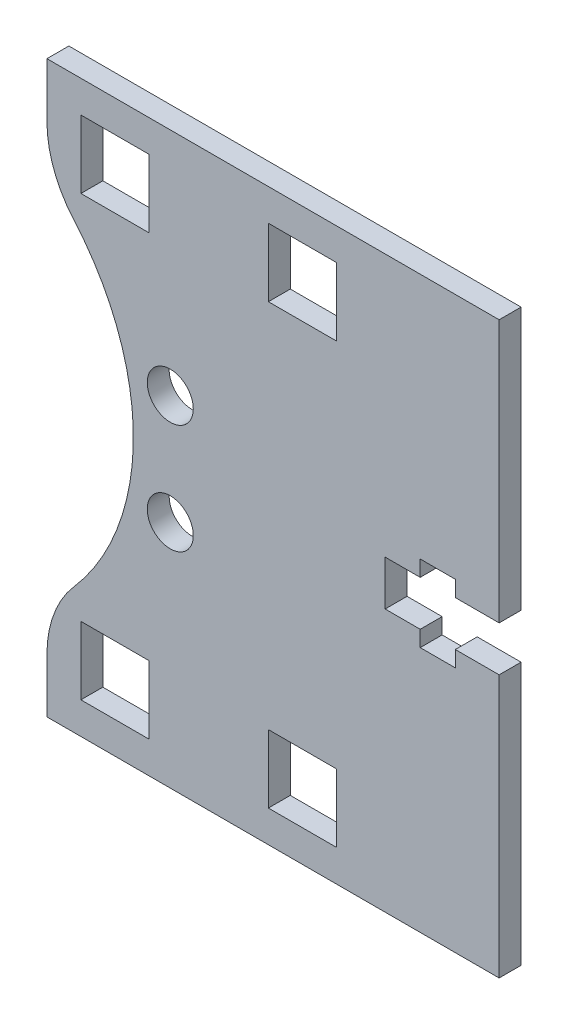
SolidWorks part; units mm, degrees
ref_plane "前视基准面" through (0, 0, 0) normal (0, 0, 1) x (1, 0, 0)
ref_plane "上视基准面" through (0, 0, 0) normal (0, 1, 0) x (1, 0, 0)
ref_plane "右视基准面" through (0, 0, 0) normal (1, 0, 0) x (0, 0, -1)
sketch "草图1" plane through (0, 0, 0) normal (0, 0, 1) x (1, 0, 0)
  line L0 (-10.3431, 0) -> (44.8563, 0) construction
  line L1 (38.2662, -5) -> (38.2662, -19.6678) construction
  line L2 (43.7162, -16.9) -> (43.7162, -23.1)
  line L3 (26.6162, -16.9) -> (32.8162, -16.9)
  line L4 (26.6162, -16.9) -> (26.6162, -23.1)
  line L5 (26.6162, -23.1) -> (32.8162, -23.1)
  line L6 (32.8162, -16.9) -> (32.8162, -23.1)
  line L7 (26.6162, -16.9) -> (32.8162, -23.1) construction
  line L8 (26.6162, -23.1) -> (32.8162, -16.9) construction
  line L9 (49.9162, -23.1) -> (43.7162, -23.1)
  line L10 (49.9162, -16.9) -> (49.9162, -23.1)
  line L11 (49.9162, -16.9) -> (43.7162, -16.9)
  line L12 (32.8162, 16.9) -> (32.8162, 23.1)
  line L13 (26.6162, 23.1) -> (32.8162, 23.1)
  line L14 (26.6162, 16.9) -> (32.8162, 16.9)
  line L15 (26.6162, 16.9) -> (26.6162, 23.1)
  line L16 (43.7162, 16.9) -> (43.7162, 23.1)
  line L17 (49.9162, 23.1) -> (43.7162, 23.1)
  line L18 (49.9162, 16.9) -> (49.9162, 23.1)
  line L19 (49.9162, 16.9) -> (43.7162, 16.9)
  line L20 (43.7162, -16.9) -> (32.8162, 16.9) construction
  line L21 (29.7162, -20) -> (29.7162, -18) construction
  line L22 (64.7662, -26) -> (23.5162, -26)
  line L23 (64.7662, -26) -> (64.7662, 26) construction
  line L24 (64.7662, 26) -> (23.5162, 26)
  line L28 (29.7162, -18) -> (46.5434, -18) construction
  line L29 (64.7662, 2.05) -> (60.7662, 2.05)
  line L30 (60.7662, 2.05) -> (60.7662, 3.5)
  line L31 (60.7662, 3.5) -> (57.5662, 3.5)
  line L32 (57.5662, 3.5) -> (57.5662, 2.05)
  line L33 (57.5662, 2.05) -> (54.3662, 2.05)
  line L34 (54.3662, 2.05) -> (54.3662, -2.05)
  line L35 (60.7662, -2.05) -> (60.7662, -3.5)
  line L36 (57.5662, -3.5) -> (57.5662, -2.05)
  line L37 (64.7662, -2.05) -> (60.7662, -2.05)
  line L38 (60.7662, -3.5) -> (57.5662, -3.5)
  line L39 (57.5662, -2.05) -> (54.3662, -2.05)
  line L43 (64.7662, 2.05) -> (64.7662, 26)
  line L47 (64.7662, -26) -> (64.7662, -2.05)
  line L54 (23.5162, -26) -> (23.5162, -16.9)
  line L55 (23.5162, 26) -> (23.5162, 16.9)
  line L56 (23.5162, 16.9) -> (23.5162, -16.9) construction
  circle A0 centre (34.7662, 5) radius 2.1
  circle A1 centre (38.1298, -18) radius 2.05 construction
  circle A2 centre (34.7662, -5) radius 2.1
  circle A3 centre (38.1298, 18) radius 2.05 construction
  arc A6 (23.5162, 16.9) -> (23.5162, -16.9) centre (9.3479, 0) cw
  point P8 (29.7162, -20)
  point P10 (38.2662, 0)
  point P19 (46.8162, -20)
  point P28 (46.8162, 20)
  point P55 (54.3662, 0)
  dimension "D2" = 30
  dimension "D7" = 52
  dimension "D9" = 4.1
  dimension "D14" = 4.2
  dimension "D1" = 5
  dimension "D3" = 3.5
  dimension "D4" = 6.2
  dimension "D5" = 6.2
  dimension "D6" = 17.1
  dimension "D8" = 40
  dimension "D10" = 3.2
  dimension "D11" = 4
  dimension "D12" = 3.5
  dimension "D13" = 2.05
extrude "凸台-拉伸1" add sketch "草图1" along normal blind 2
fillet "圆角1" radius 10 2 edges at (23.5162, -16.9, 1) (23.5162, 16.9, 1)
